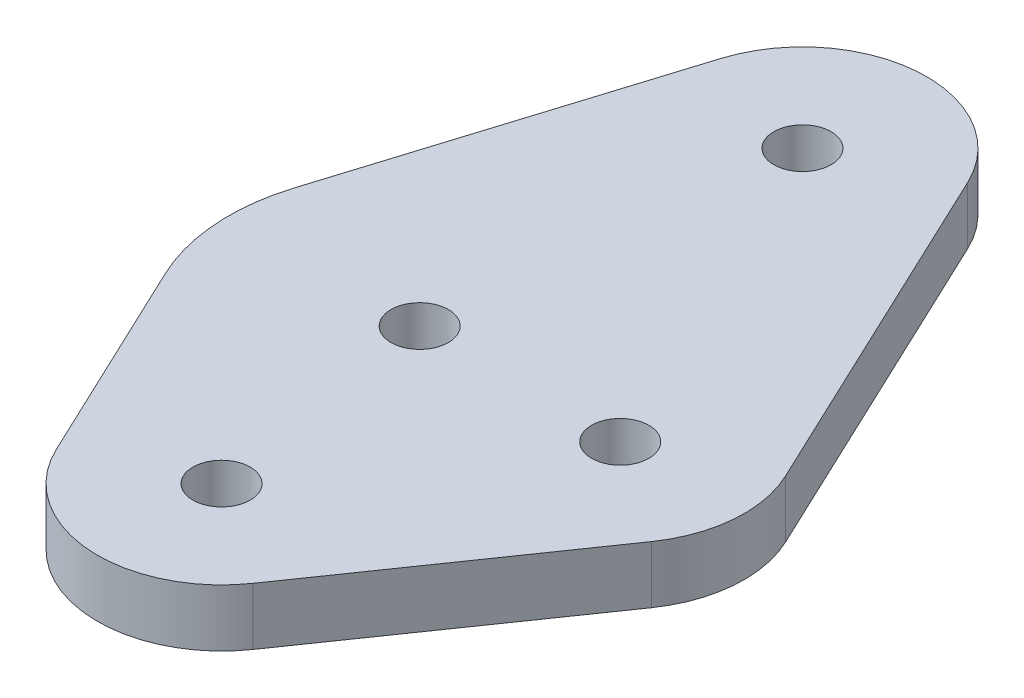
SolidWorks part; units mm, degrees
ref_plane "正面" through (0, 0, 0) normal (0, 0, 1) x (1, 0, 0)
ref_plane "平面" through (0, 0, 0) normal (0, 1, 0) x (1, 0, 0)
ref_plane "右側面" through (0, 0, 0) normal (1, 0, 0) x (0, 0, -1)
sketch "ｽｹｯﾁ1" plane through (0, 0, 0) normal (0, 1, 0) x (1, 0, 0)
  line L0 (-2.6652, 20.8602) -> (5.8773, 2.7763)
  line L1 (5.343, -3.7017) -> (-3.1995, -16.0316)
  line L2 (-14.7493, 20.0138) -> (-20.0491, 2.9691)
  line L3 (-19.5406, -4.274) -> (-14.4188, -15.108)
  circle A0 centre (0, 0) radius 1.5
  circle A1 centre (-8.5424, 18.0839) radius 1.5
  circle A2 centre (-8.5424, -12.3299) radius 1.5
  arc A5 (-2.6652, 20.8602) -> (-14.7493, 20.0138) centre (-8.5424, 18.0839) ccw
  arc A6 (-14.4188, -15.108) -> (-3.1995, -16.0316) centre (-8.5424, -12.3299) ccw
  arc A7 (5.343, -3.7017) -> (5.8773, 2.7763) centre (0, 0) ccw
  arc A8 (-20.0491, 2.9691) -> (-19.5406, -4.274) centre (-10.5, 0) ccw
  circle A9 centre (-10.5, 0) radius 1.5
  point P9 (0, 0)
  point P14 (0, 0)
  dimension "D1" = 3
  dimension "D4" = 5
  dimension "D7" = 10.5
  dimension "D5" = 10
  dimension "D2" = 20
  dimension "D3" = 15
  dimension "D6" = 120
extrude "ﾎﾞｽ - 押し出し1" add sketch "ｽｹｯﾁ1" along normal blind 3
